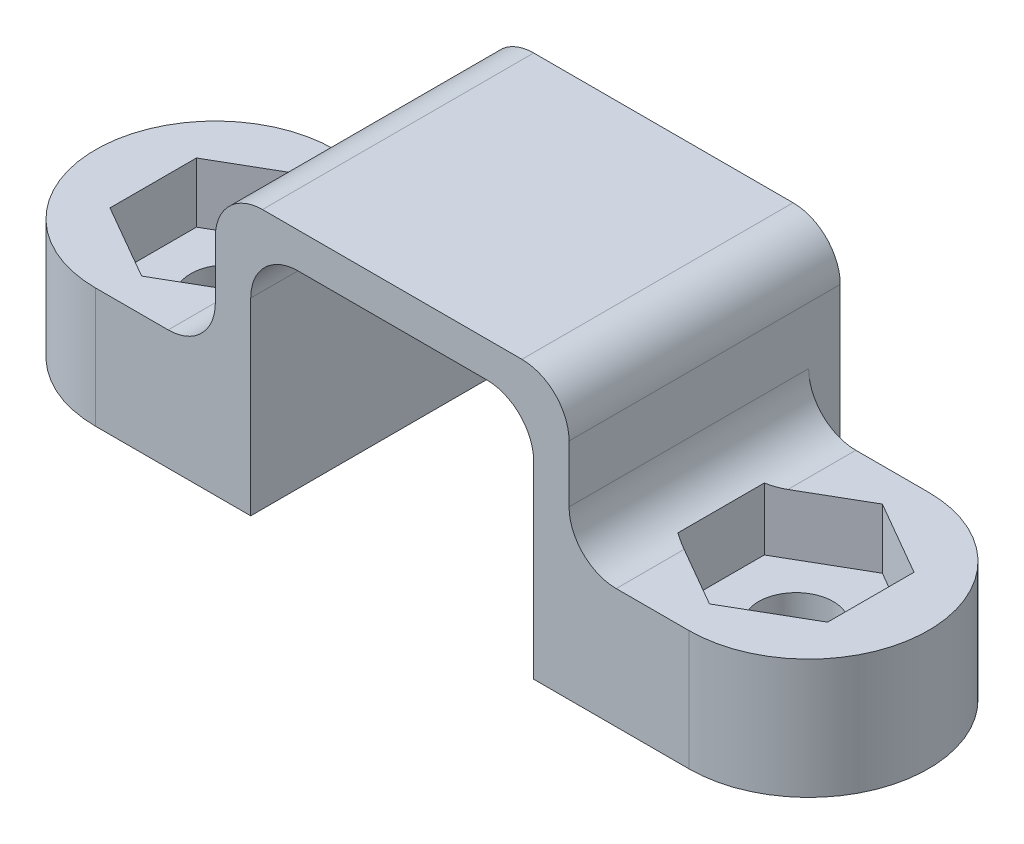
SolidWorks part; units mm, degrees
ref_plane "Front Plane" through (0, 0, 0) normal (0, 0, 1) x (1, 0, 0)
ref_plane "Top Plane" through (0, 0, 0) normal (0, 1, 0) x (1, 0, 0)
ref_plane "Right Plane" through (0, 0, 0) normal (1, 0, 0) x (0, 0, -1)
sketch "Sketch1" plane through (0, 0, 0) normal (0, 0, 1) x (1, 0, 0)
  line L0 (1.5, -11.5) -> (1.5, -1.5)
  line L1 (0, 0) -> (15, 0)
  line L2 (0, 0) -> (0, -11.5)
  line L3 (0, -11.5) -> (15, -11.5) construction
  line L4 (15, 0) -> (15, -11.5)
  line L5 (1.5, -1.5) -> (13.5, -1.5)
  line L6 (13.5, -1.5) -> (13.5, -11.5)
  line L7 (1.5, -11.5) -> (0, -11.5)
  line L8 (13.5, -11.5) -> (15, -11.5)
  dimension "D1" = 11.5
  dimension "D2" = 15
  dimension "D3" = 12
  dimension "D4" = 1.5
extrude "Boss-Extrude1" add sketch "Sketch1" along normal blind 11.5
fillet "Fillet1" radius 2 2 edges at (1.5, -1.5, 5.75) (13.5, -1.5, 5.75)
ref_plane "Plane1" through (0, -11.5, 0) normal (0, 1, 0) x (1, 0, 0)
sketch "Sketch2" plane through (0, -11.5, 0) normal (0, 1, 0) x (1, 0, 0)
  line L0 (15, -11.5) -> (20.08, -11.5)
  line L2 (20.08, -11.5) -> (20.08, -1.34) construction
  line L3 (20.08, -1.34) -> (15, -1.34)
  line L4 (15, -11.5) -> (15, 0) construction
  line L5 (7.5, -11.5) -> (7.5, 0) construction
  line L6 (-5.08, -11.5) -> (-5.08, -1.34) construction
  line L7 (-5.08, -1.34) -> (0, -1.34)
  line L8 (0, -11.5) -> (-5.08, -11.5)
  line L9 (3.5, -11.5) -> (11.5, -11.5)
  line L10 (3.5, 0) -> (3.5, -11.5)
  line L11 (11.5, 0) -> (3.5, 0)
  line L12 (11.5, -11.5) -> (11.5, 0)
  line L13 (3.5, -11.5) -> (11.5, -11.5) construction
  line L14 (3.5, 0) -> (3.5, -11.5) construction
  line L15 (11.5, 0) -> (3.5, 0) construction
  line L16 (11.5, -11.5) -> (11.5, 0) construction
  line L17 (0, -11.5) -> (0, -1.34)
  line L18 (15, -11.5) -> (15, -1.34)
  line L19 (15, -1.34) -> (15.0338, -1.39)
  arc A0 (20.08, -11.5) -> (20.08, -1.34) centre (20.08, -6.42) ccw
  arc A1 (-5.08, -11.5) -> (-5.08, -1.34) centre (-5.08, -6.42) cw
  dimension "D2" = 5.08
  dimension "D1" = 10.16
  dimension "D3" = 0
extrude "Boss-Extrude2" add sketch "Sketch2" along normal blind 5.08
fillet "Fillet2" radius 2 2 edges
fillet "Fillet3" radius 2 2 edges at (15, 0, 5.75) (0, 0, 5.75)
sketch "Sketch3" plane through (0, -11.5, 0) normal (0, 1, 0) x (1, 0, 0)
  line L0 (17, -1.34) -> (17, -11.5) construction
  line L1 (-2, -11.5) -> (-2, -1.34) construction
  line L2 (17, -1.34) -> (17, -11.5) construction
  line L3 (-2, -11.5) -> (-2, -1.34) construction
  line L4 (19.54, -6.42) -> (17, -6.42) construction
  line L5 (7.5, 0) -> (7.5, -11.5) construction
  line L9 (2, -11.5) -> (13, -11.5)
  line L10 (13, -11.5) -> (13, 0)
  line L11 (13, 0) -> (2, 0)
  line L12 (2, 0) -> (2, -11.5)
  line L13 (2, -11.5) -> (13, -11.5) construction
  line L14 (13, -11.5) -> (13, 0) construction
  line L15 (13, 0) -> (2, 0) construction
  line L16 (2, 0) -> (2, -11.5) construction
  circle A0 centre (19.54, -6.42) radius 1.5875
  circle A1 centre (-4.54, -6.42) radius 1.5875
  dimension "D1" = 3.175
  dimension "D2" = 0
  dimension "D3" = 2.54
extrude "Cut-Extrude1" cut sketch "Sketch3" along normal through all
sketch "Sketch6" plane through (0, -11.5, 0) normal (0, 1, 0) x (1, 0, 0)
  line L0 (2, 0) -> (2, -11.5) construction
  line L7 (3.5, -11.5) -> (11.5, -11.5) construction
  line L8 (3.5, 0) -> (11.5, 0) construction
  line L9 (3.5, -11.5) -> (11.5, -11.5) construction
  line L10 (3.5, 0) -> (11.5, 0) construction
  line L11 (7.5, -11.5) -> (7.5, 0) construction
  line L18 (13, -11.5) -> (13, 0) construction
  line L19 (-1.365, -4.5869) -> (-4.54, -2.7538)
  line L20 (-4.54, -2.7538) -> (-7.715, -4.5869)
  line L21 (-7.715, -4.5869) -> (-7.715, -8.2531)
  line L22 (-7.715, -8.2531) -> (-4.54, -10.0862)
  line L23 (-4.54, -10.0862) -> (-1.365, -8.2531)
  line L24 (-1.365, -8.2531) -> (-1.365, -4.5869)
  line L25 (22.715, -8.2531) -> (22.715, -4.5869)
  line L26 (22.715, -4.5869) -> (19.54, -2.7538)
  line L27 (19.54, -2.7538) -> (16.365, -4.5869)
  line L28 (16.365, -4.5869) -> (16.365, -8.2531)
  line L29 (16.365, -8.2531) -> (19.54, -10.0862)
  line L30 (19.54, -10.0862) -> (22.715, -8.2531)
  circle A4 centre (-4.54, -6.42) radius 3.175 construction
  circle A5 centre (19.54, -6.42) radius 3.175 construction
  dimension "D1" = 6.35
  dimension "D2" = 6.35
ref_plane "Plane2" through (0, -6.42, 0) normal (0, 1, 0) x (1, 0, 0)
extrude "Cut-Extrude3" cut sketch "Sketch6" against normal blind 2.54 and the other way blind 2 from offset 5.08
equation "\"1.5.00mm\"=2"
